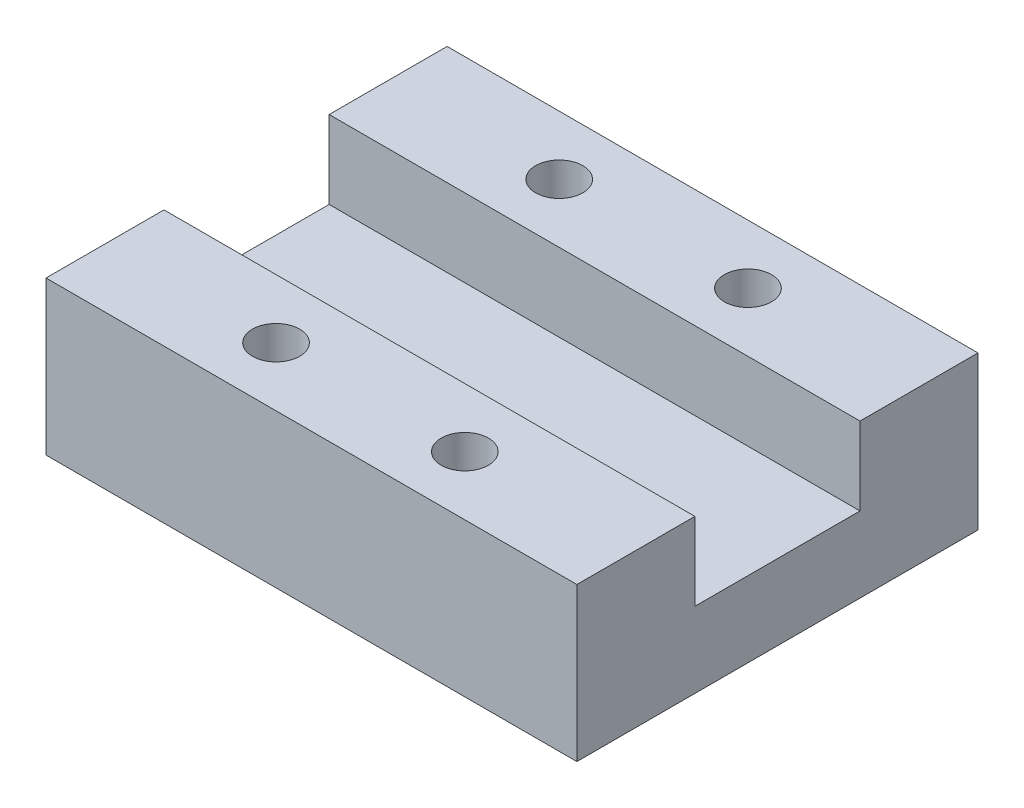
SolidWorks part; units mm, degrees
ref_plane "前视基准面" through (0, 0, 0) normal (0, 0, 1) x (1, 0, 0)
ref_plane "上视基准面" through (0, 0, 0) normal (0, 1, 0) x (1, 0, 0)
ref_plane "右视基准面" through (0, 0, 0) normal (1, 0, 0) x (0, 0, -1)
sketch "草图1" plane through (0, 0, 0) normal (0, 1, 0) x (1, 0, 0)
  line L1 (-11.25, 8.5) -> (11.25, 8.5)
  line L2 (-11.25, 8.5) -> (-11.25, -8.5)
  line L3 (-11.25, -8.5) -> (11.25, -8.5)
  line L4 (11.25, 8.5) -> (11.25, -8.5)
  line L5 (-11.25, 8.5) -> (11.25, -8.5) construction
  line L6 (-11.25, -8.5) -> (11.25, 8.5) construction
  line L7 (-4, 6) -> (4, 6) construction
  line L8 (-4, 6) -> (-4, -6) construction
  line L9 (-4, -6) -> (4, -6) construction
  line L10 (4, 6) -> (4, -6) construction
  line L11 (-4, 6) -> (4, -6) construction
  line L12 (-4, -6) -> (4, 6) construction
  circle A0 centre (4, 6) radius 1
  circle A1 centre (-4, 6) radius 1
  circle A2 centre (-4, -6) radius 1
  circle A3 centre (4, -6) radius 1
  point P0 (0, 0)
  point P6 (0, 0)
  dimension "D5" = 2
  dimension "D6" = 2
  dimension "D7" = 2
  dimension "D8" = 2
  dimension "D1" = 17
  dimension "D2" = 22.5
  dimension "D3" = 8
  dimension "D4" = 12
extrude "凸台-拉伸1" add sketch "草图1" along normal blind 3.2
ref_plane "基准面1" through (0, 3.2, 0) normal (0, 1, 0) x (1, 0, 0)
sketch "草图2" plane through (0, 3.2, 0) normal (0, 1, 0) x (1, 0, 0)
  line L0 (11.25, -8.5) -> (11.25, 8.5) construction
  line L1 (-11.25, 8.5) -> (11.25, 8.5)
  line L2 (-11.25, 8.5) -> (-11.25, 3.5)
  line L3 (-11.25, 3.5) -> (11.25, 3.5)
  line L4 (11.25, 8.5) -> (11.25, 3.5)
  line L6 (-11.25, -8.5) -> (11.25, -8.5)
  line L7 (-11.25, -8.5) -> (-11.25, -3.5)
  line L8 (-11.25, -3.5) -> (11.25, -3.5)
  line L9 (11.25, -8.5) -> (11.25, -3.5)
  circle A0 centre (-4, 6) radius 1
  circle A1 centre (4, 6) radius 1
  circle A2 centre (-4, -6) radius 1
  circle A3 centre (4, -6) radius 1
  dimension "D1" = 5
  dimension "D2" = 5
extrude "凸台-拉伸2" add sketch "草图2" along normal blind 3.3
